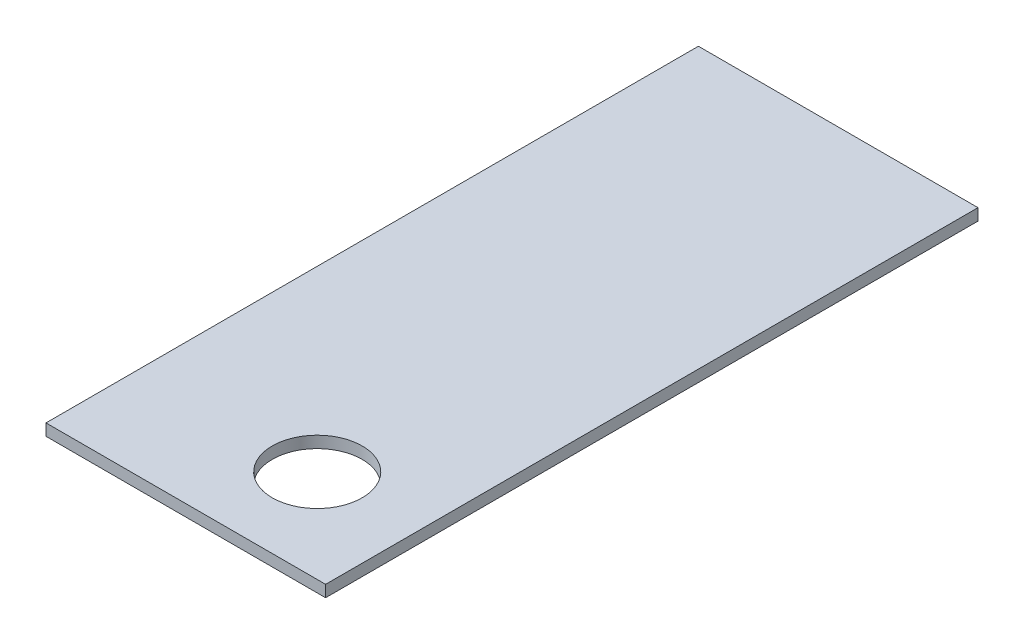
SolidWorks part; units mm, degrees
ref_plane "Front Plane" through (0, 0, 0) normal (0, 0, 1) x (1, 0, 0)
ref_plane "Top Plane" through (0, 0, 0) normal (0, 1, 0) x (1, 0, 0)
ref_plane "Right Plane" through (0, 0, 0) normal (1, 0, 0) x (0, 0, -1)
sketch "Sketch1" plane through (0, 0, 0) normal (0, 1, 0) x (1, 0, 0)
  line L1 (0, 0) -> (76.2, 0)
  line L2 (0, 0) -> (0, 177.8)
  line L3 (0, 177.8) -> (76.2, 177.8)
  line L4 (76.2, 0) -> (76.2, 177.8)
  circle A0 centre (48.514, 25.4) radius 12.25
  dimension "D3" = 27.686
  dimension "D4" = 24.5
  dimension "D1" = 177.8
  dimension "D2" = 76.2
  dimension "D5" = 25.4
extrude "Boss-Extrude1" add sketch "Sketch1" along normal blind 3.175
